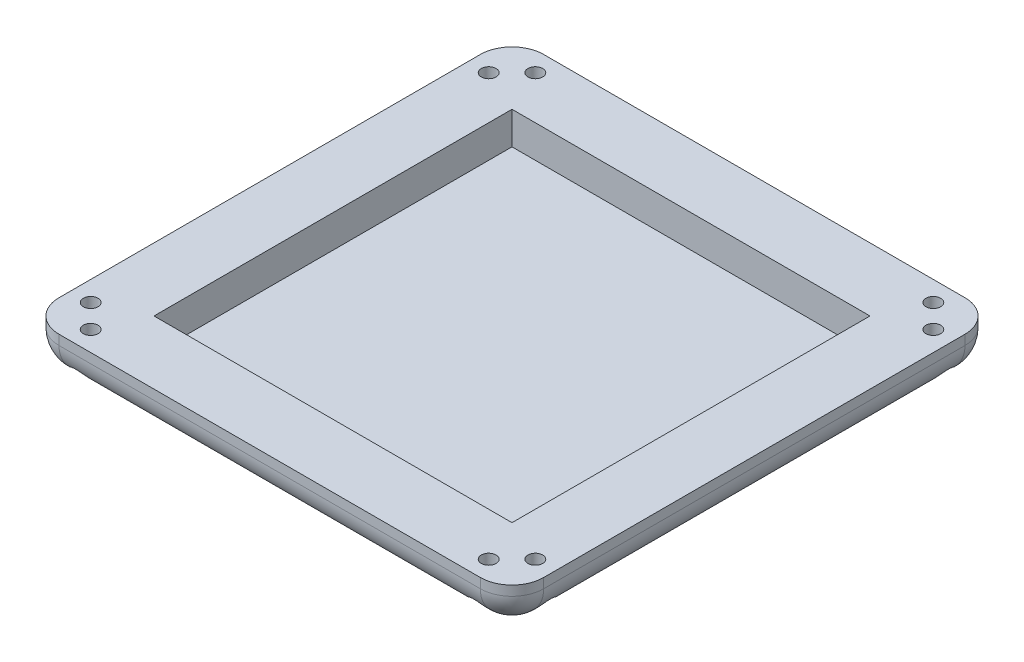
SolidWorks part; units mm, degrees
material "ПК/АБС"
ref_plane "Спереди" through (0, 0, 0) normal (0, 0, 1) x (1, 0, 0)
ref_plane "Сверху" through (0, 0, 0) normal (0, 1, 0) x (1, 0, 0)
ref_plane "Справа" through (0, 0, 0) normal (1, 0, 0) x (0, 0, -1)
sketch "Эскиз1" plane through (0, 0, 0) normal (0, 1, 0) x (1, 0, 0)
  line L1 (-35.6, 40.95) -> (35.6, 40.95)
  line L2 (-40.95, 35.6) -> (-40.95, -35.6)
  line L3 (-35.6, -40.95) -> (35.6, -40.95)
  line L4 (40.95, 35.6) -> (40.95, -35.6)
  line L5 (-40.95, 40.95) -> (40.95, -40.95) construction
  line L6 (-40.95, -40.95) -> (40.95, 40.95) construction
  arc A0 (-40.95, -35.6) -> (-35.6, -40.95) centre (-35.6, -35.6) ccw
  arc A1 (35.6, -40.95) -> (40.95, -35.6) centre (35.6, -35.6) ccw
  arc A2 (40.95, 35.6) -> (35.6, 40.95) centre (35.6, 35.6) ccw
  arc A3 (-35.6, 40.95) -> (-40.95, 35.6) centre (-35.6, 35.6) ccw
  point P0 (0, 0)
  dimension "D1" = 5.35
extrude "Бобышка-Вытянуть1" add sketch "Эскиз1" against normal blind 7
sketch "Эскиз2" plane through (0, 0, 0) normal (0, 1, 0) x (-1, 0, 0)
  line L1 (-30.25, 30.25) -> (30.25, 30.25)
  line L2 (-30.25, 30.25) -> (-30.25, -30.25)
  line L3 (-30.25, -30.25) -> (30.25, -30.25)
  line L4 (30.25, 30.25) -> (30.25, -30.25)
  line L5 (-30.25, 30.25) -> (30.25, -30.25) construction
  line L6 (-30.25, -30.25) -> (30.25, 30.25) construction
  point P0 (0, 0)
extrude "Вырез-Вытянуть1" cut sketch "Эскиз2" against normal blind 5.5
fillet "Скругление2" radius 5.35 8 edges at (-39.383, -7, 39.383) (-39.383, -7, -39.383) (39.383, -7, -39.383) (39.383, -7, 39.383) (-40.95, -7, 0) (0, -7, -40.95) (40.95, -7, 0) (0, -7, 40.95)
sketch "Эскиз4" plane through (0, -7, 0) normal (0, -1, 0) x (1, 0, 0)
  point P0 (33.63, 37.57)
  point P1 (37.57, -33.63)
  point P2 (37.57, 33.63)
  point P3 (-33.63, -37.57)
  point P4 (33.63, -37.57)
  point P9 (-37.57, 33.63)
  point P10 (-37.57, -33.63)
  point P12 (-33.63, 37.57)
hole_wizard "Цековка для  винта с заклепочной головкой M2.51" positions "Эскиз6" profile "Эскиз7" counterbore size "M2.5" standard "ISO" end condition through all
sketch "Эскиз6" plane through (0, -7, 0) normal (0, -1, 0) x (-1, 0, 0)
  point P0 (37.57, 33.63)
  point P4 (33.63, 37.57)
  point P8 (37.57, -33.63)
  point P12 (33.63, -37.57)
  point P16 (-33.63, -37.57)
  point P20 (-37.57, -33.63)
  point P24 (-37.57, 33.63)
  point P28 (-33.63, 37.57)
sketch "Эскиз7" plane through (-37.57, -7, -33.63) normal (1, 0, 0) x (0, 0, -1)
  line L0 (0, 0) -> (0, 7)
  line L1 (0, 7) -> (1.25, 7)
  line L3 (1.25, 7) -> (1.25, 4)
  line L4 (1.25, 4) -> (2.5, 4)
  line L5 (2.5, 4) -> (2.5, 0)
  line L7 (2.5, 0) -> (0, 0)
  line L11 (0, -6.35) -> (0, 107.95) construction
  dimension "Диаметр сквозного отверстия" = 2.5
  dimension "Глубина сквозного отверстия" = 7
  dimension "Диаметр цековки" = 5
  dimension "Глубина цековки" = 4
